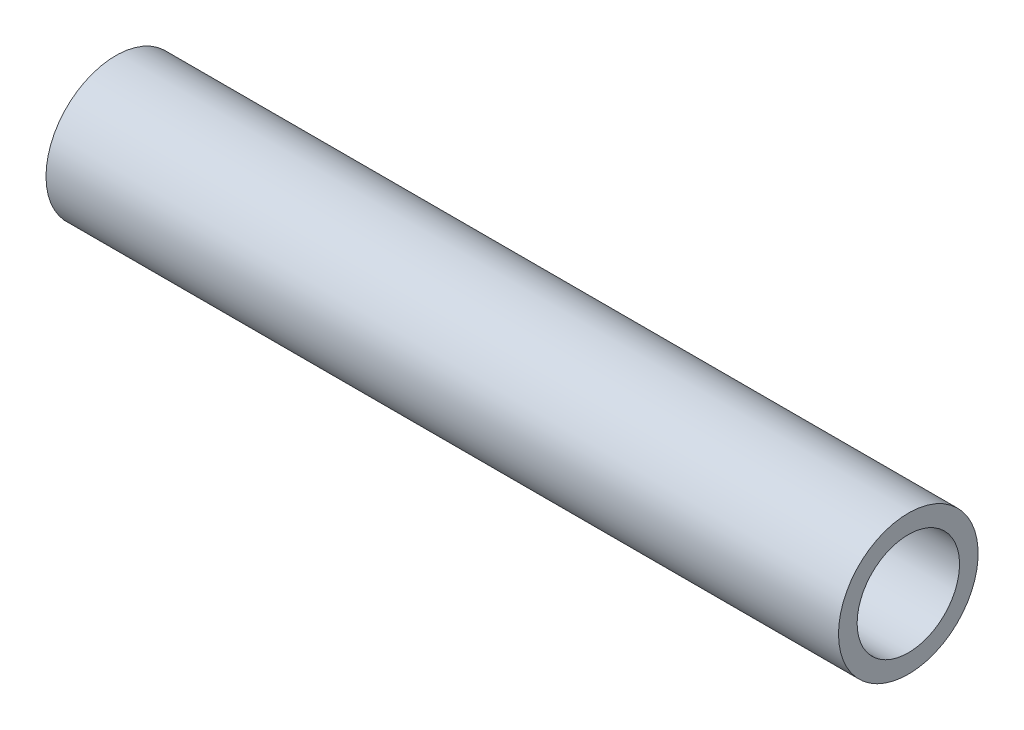
SolidWorks part; units mm, degrees
ref_plane "Front Plane" through (0, 0, 0) normal (0, 0, 1) x (1, 0, 0)
ref_plane "Top Plane" through (0, 0, 0) normal (0, 1, 0) x (1, 0, 0)
ref_plane "Right Plane" through (0, 0, 0) normal (1, 0, 0) x (0, 0, -1)
sketch "Axial profile (mm)" plane through (0, 0, 0) normal (0, 0, 1) x (1, 0, 0)
  line L0 (-110, 0) -> (75, 0) construction
  line L1 (0, 1.65) -> (25.541, 1.65)
  line L2 (25.541, 1.65) -> (25.541, 2.25)
  line L3 (25.541, 2.25) -> (0, 2.25)
  line L4 (0, 2.25) -> (0, 1.65)
revolve "Full revolution" add sketch "Axial profile (mm)" angle 360 about L0
